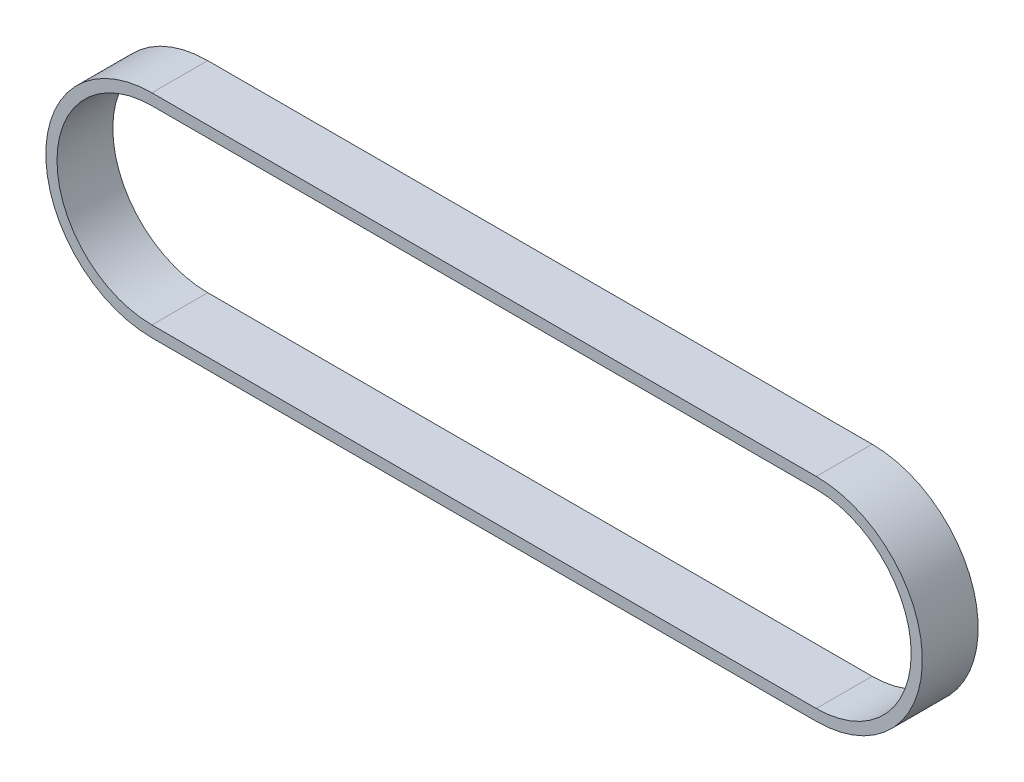
SolidWorks part; units mm, degrees
ref_plane "前视基准面" through (0, 0, 0) normal (0, 0, 1) x (1, 0, 0)
ref_plane "上视基准面" through (0, 0, 0) normal (0, 1, 0) x (1, 0, 0)
ref_plane "右视基准面" through (0, 0, 0) normal (1, 0, 0) x (0, 0, -1)
other "Configuration Table"
sketch "草图1" plane through (0, 0, 0) normal (0, 0, 1) x (1, 0, 0)
  line L0 (-15.1422, 0) -> (103.8578, 0) construction
  line L1 (-15.1422, 17) -> (103.8578, 17)
  line L2 (-15.1422, -17) -> (103.8578, -17)
  arc A0 (-15.1422, 17) -> (-15.1422, -17) centre (-15.1422, 0) ccw
  arc A1 (103.8578, -17) -> (103.8578, 17) centre (103.8578, 0) ccw
  point P3 (44.3578, 0)
  dimension "D1" = 17
  dimension "D2" = 119
extrude "拉伸-薄壁1" add sketch "草图1" along normal mid plane 10 thin thin type one direction wall 2
